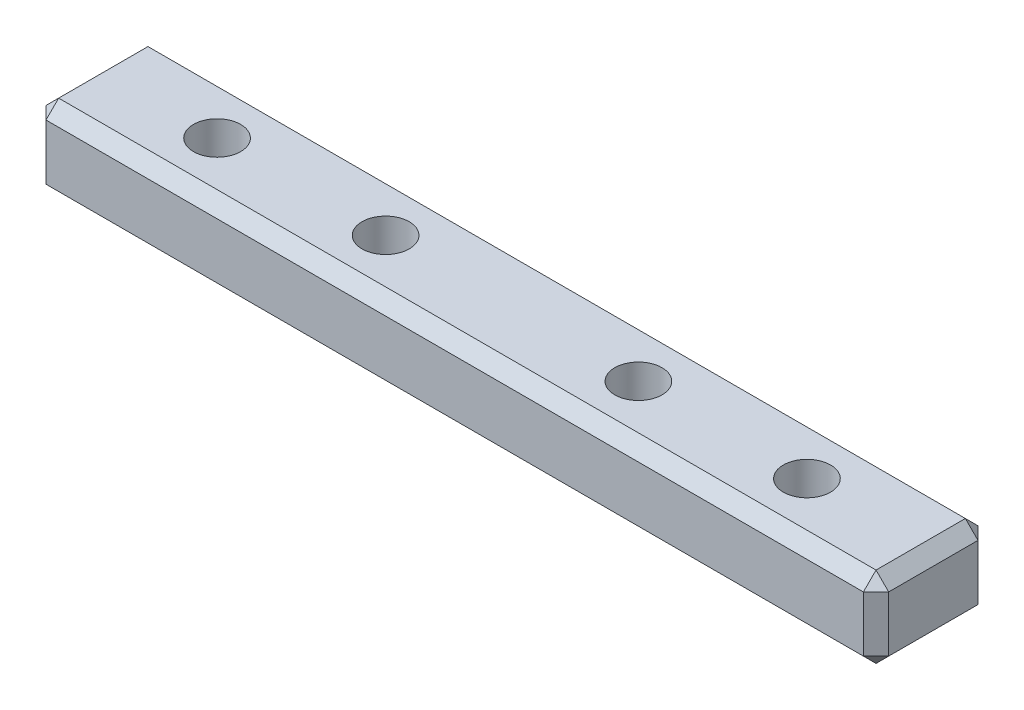
SolidWorks part; units mm, degrees
material "ABS generico"
ref_plane "Piano frontale" through (0, 0, 0) normal (0, 0, 1) x (1, 0, 0)
ref_plane "Piano superiore" through (0, 0, 0) normal (0, 1, 0) x (1, 0, 0)
ref_plane "Piano destro" through (0, 0, 0) normal (1, 0, 0) x (0, 0, -1)
ref_plane "Piano1" through (0, 4.8, 0) normal (0, 1, 0) x (1, 0, 0)
sketch "Schizzo1" plane through (0, 4.8, 0) normal (0, 1, 0) x (1, 0, 0)
  line L0 (50, -6.8) -> (50, 6.8)
  line L1 (50, 6.8) -> (-50, 6.8)
  line L2 (-50, 6.8) -> (-50, -6.8)
  line L3 (-50, -6.8) -> (50, -6.8)
  dimension "D1" = 100
  dimension "D2" = 13.6
extrude "Estrusione-Estrusione1" add sketch "Schizzo1" against normal blind 9.6
hole_wizard "Foro Ø5.6 (5.6)-1" positions "Schizzo3" profile "Schizzo2" hole size "Ø5.6" standard "Ansi Metric"
sketch "Schizzo3" plane through (0, -4.8, 0) normal (0, -1, 0) x (-1, 0, 0)
  point P0 (-35, 0)
  point P1 (35, 0)
  point P2 (-15, 0)
  point P3 (15, 0)
sketch "Schizzo2" plane through (35, -4.8, 0) normal (1, 0, 0) x (0, 0, -1)
  line L0 (0, 0) -> (0, 9.6)
  line L1 (0, 9.6) -> (2.8, 9.6)
  line L2 (2.8, 9.6) -> (2.8, 0)
  line L5 (2.8, 0) -> (0, 0)
  line L11 (0, -6.35) -> (0, 107.95) construction
  dimension "Thru Hole Dia." = 5.6
  dimension "Thru Hole Depth" = 9.6
chamfer "Smusso1" distance 1.5 angle 45 12 edges at (-50, -4.8, 0) (-50, 0, 6.8) (-50, 0, -6.8) (-50, 4.8, 0) (50, 4.8, 0) (0, 4.8, -6.8) (50, 0, -6.8) (0, 4.8, 6.8) (50, 0, 6.8) (0, -4.8, 6.8) (50, -4.8, 0) (0, -4.8, -6.8)
